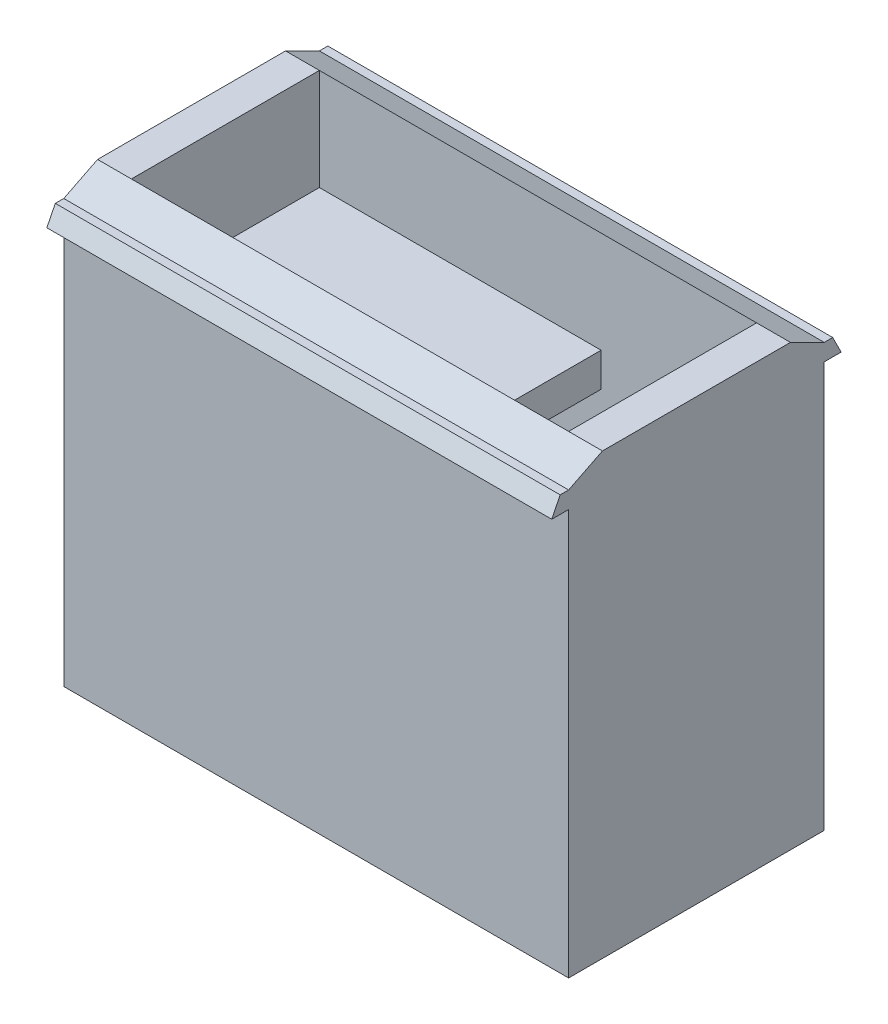
SolidWorks part; units mm, degrees
ref_plane "Front Plane" through (0, 0, 0) normal (0, 0, 1) x (1, 0, 0)
ref_plane "Top Plane" through (0, 0, 0) normal (0, 1, 0) x (1, 0, 0)
ref_plane "Right Plane" through (0, 0, 0) normal (1, 0, 0) x (0, 0, -1)
sketch "Sketch1" plane through (0, 0, 0) normal (0, 1, 0) x (1, 0, 0)
  line L0 (-13, 0) -> (-13, -1)
  line L1 (0, 0) -> (-13, 0)
  line L2 (0, 0) -> (0, 5.56)
  line L3 (0, 5.56) -> (-13, 5.56)
  line L4 (-13, 0) -> (-13, 5.56)
  line L5 (-13, -1) -> (0, -1)
  line L6 (0, 0) -> (1, 0)
  line L7 (0, -1) -> (1, -1)
  line L8 (1, -1) -> (1, 0)
  line L9 (1, 5.56) -> (1, 6.56)
  line L10 (1, 5.56) -> (1, 0)
  line L11 (1, 6.56) -> (-12.932, 6.56)
  line L12 (-12.932, 6.56) -> (-13.932, 6.56)
  line L13 (-13.932, 6.56) -> (-13.932, -1)
  line L14 (-13.932, -1) -> (-13, -1)
extrude "Boss-Extrude1" add sketch "Sketch1" along normal blind 10 contours L13 L14 L0 L4 L3 L2 L6 L10 L9 L11 L12 | L7 L8 L6 L1 L0 L5
sketch "Sketch2" plane through (0, 10, 0) normal (0, 1, 0) x (1, 0, 0)
  line L0 (-6.466, -1) -> (-6.466, 6.56)
  line L1 (-13.932, -1) -> (1, -1)
  line L2 (-13.932, -1) -> (-13.932, 6.56)
  line L3 (-13.932, 6.56) -> (1, 6.56)
  line L4 (1, -1) -> (1, 6.56)
  line L5 (-6.466, 2.78) -> (1, 2.78)
  line L6 (-6.466, 2.78) -> (-2.733, 2.78)
  line L7 (-2.733, 2.78) -> (-4.5995, 2.78)
  line L8 (-4.5995, 2.78) -> (-4.5995, 6.56)
  line L9 (-4.5995, 6.56) -> (-4.5995, -1)
  line L10 (-6.466, 6.56) -> (-13.932, 6.56)
  line M5 (-13.932, -1) -> (1, -1)
  line M7 (1, 6.56) -> (-13.932, 6.56)
  line M8 (-13.932, 6.56) -> (-13.932, -1)
  line M9 (0, 0) -> (-13, 0)
  line M10 (-13, 0) -> (-13, 5.56)
  line M11 (-13, 5.56) -> (0, 5.56)
extrude "Boss-Extrude2" add sketch "Sketch2" against normal blind 1 contours L0 M9 M11 M10 | L5 L8 L0 M11 | L9 L5 L0 M9 | L0 M5 M9 M10 M11 M7 M8 | L9 L0 M9 M5 | L8 L3 L0 M11
sketch "Sketch3" plane through (0, 10, 0) normal (0, 1, 0) x (1, 0, 0)
  line L0 (-13.932, 6.56) -> (-12.932, 6.56)
  line L1 (-13.932, -1) -> (1, -1)
  line L2 (-13.932, -1) -> (-13.932, 6.56)
  line L3 (-13.932, 6.56) -> (1, 6.56)
  line L4 (1, -1) -> (1, 6.56)
  line L5 (-12.932, 6.56) -> (-12.932, -1)
  line L6 (-12.932, -1) -> (-12.932, 0)
  line L7 (-12.932, 0) -> (-4.5995, 0)
  line L8 (-4.5995, 0) -> (0, 0)
  line L9 (0, 0) -> (0, 5.56)
  line L10 (0, 5.56) -> (-4.5995, 5.56)
  line L11 (-4.5995, 5.56) -> (-12.932, 5.56)
  line M6 (0, 0) -> (-4.5995, 0)
  line M8 (-4.5995, 5.56) -> (0, 5.56)
  line M9 (0, 5.56) -> (0, 0)
  line M10 (1, 6.56) -> (-13.932, 6.56)
  line M11 (-13.932, 6.56) -> (-13.932, -1)
  line M12 (-13.932, -1) -> (1, -1)
  line M13 (1, -1) -> (1, 6.56)
extrude "Boss-Extrude3" add sketch "Sketch3" along normal blind 3 contours L11 L7 L5 L1 M8 M9 M6 M13 M10 | L5 M10 M11 M12
sketch "Sketch4" plane through (0, 0, 1) normal (0, 0, 1) x (1, 0, 0)
  line L0 (1, 13) -> (1, 0) construction
  line L1 (-13.932, 13) -> (1, 13)
  line L2 (-13.932, 13) -> (-13.932, 12)
  line L3 (-13.932, 12) -> (1, 12)
  line L4 (1, 13) -> (1, 12)
extrude "Boss-Extrude4" add sketch "Sketch4" along normal blind 1
sketch "Sketch5" plane through (0, 0, -6.56) normal (0, 0, -1) x (-1, 0, 0)
  line L0 (13.932, 13) -> (13.932, 0) construction
  line L1 (-1, 13) -> (13.932, 13)
  line L2 (-1, 13) -> (-1, 12.0013)
  line L3 (-1, 12.0013) -> (13.932, 12.0013)
  line L4 (13.932, 13) -> (13.932, 12.0013)
extrude "Boss-Extrude5" add sketch "Sketch5" along normal blind 1
sketch "Sketch6" plane through (-13.932, 0, 0) normal (-1, 0, 0) x (0, 0, 1)
  line L0 (2, 12) -> (1, 12)
  line L1 (1, 12) -> (1, 13)
  line L2 (-7.56, 13) -> (2, 13) construction
  line L3 (1, 13) -> (2, 12)
  line L4 (2, 13) -> (1, 13)
  line L5 (2, 13) -> (2, 12)
  line L6 (-6.56, 12.0013) -> (-6.56, 13)
  line L7 (-6.56, 13) -> (-7.56, 13)
  line L8 (-7.56, 13) -> (-7.56, 12.0013)
  line L9 (-7.56, 12.0013) -> (-6.56, 12.0013)
  line L10 (-7.56, 13) -> (-6.56, 13)
  line L11 (-6.56, 13) -> (-7.56, 12.0013)
  line M1 (2, 13) -> (-7.56, 13)
  line M2 (-7.56, 13) -> (-7.56, 12.0013)
  line M8 (2, 12) -> (2, 13)
extrude "Cut-Extrude1" cut sketch "Sketch6" against normal blind 15 contours L11 M1 M2 | L3 M1 M8
sketch "Sketch7" plane through (1, 0, 0) normal (1, 0, 0) x (0, 0, -1)
  line L0 (-1, 13) -> (-1, 12)
  line L1 (-1, 12) -> (-1.5, 12)
  line L2 (-2, 12) -> (-1, 12) construction
  line L3 (-1.5, 12) -> (-1, 13)
  line L4 (-2, 12) -> (-1, 13)
  line L5 (-1.5, 12) -> (-2, 12)
  line L6 (6.56, 13) -> (6.56, 12.0013)
  line L7 (6.56, 12.0013) -> (7.06, 12.0013)
  line L8 (7.56, 12.0013) -> (6.56, 12.0013) construction
  line L9 (7.06, 12.0013) -> (6.56, 13)
  line L10 (7.56, 12.0013) -> (6.56, 13)
  line L11 (7.06, 12.0013) -> (7.56, 12.0013)
  line M1 (6.56, 12.0013) -> (7.56, 12.0013)
  line M2 (7.56, 12.0013) -> (6.56, 13)
  line M4 (-1, 13) -> (-2, 12)
  line M5 (-2, 12) -> (-1, 12)
extrude "Cut-Extrude2" cut sketch "Sketch7" against normal blind 15 contours L3 M5 M4 | L9 M1 M2
sketch "Sketch8" plane through (1, 0, 0) normal (1, 0, 0) x (0, 0, -1)
  line L0 (-1, 12) -> (6.56, 12.0013)
  line L1 (6.56, 12.0013) -> (6.56, 0) construction
sketch "Sketch9" plane through (0, 0, -6.56) normal (0, 0, -1) x (-1, 0, 0)
  line L0 (-1, 6.0007) -> (13.932, 6.0007)
  line L1 (-1, 12.0013) -> (-1, 0) construction
  line L2 (13.932, 12.0013) -> (13.932, 0) construction
  line L3 (-1, 12) -> (-1, 13) construction
sketch "Sketch10" plane through (1, 0, 0) normal (1, 0, 0) x (0, 0, -1)
  line L0 (-1.5, 12) -> (-1, 12)
  line L1 (5.56, 13) -> (5.56, 0) construction
sketch "Sketch11" plane through (0, 0, -5.56) normal (0, 0, 1) x (1, 0, 0)
  line L0 (-5.4355, 10) -> (-5.4355, 13)
  line L2 (-4.5995, 10) -> (-12.932, 10) construction
  line L3 (0, 13) -> (-12.932, 13) construction
sketch "Sketch12" plane through (-13.932, 0, 0) normal (-1, 0, 0) x (0, 0, 1)
  line L0 (-6.56, 12.0013) -> (-6.56, 13)
  line L1 (-6.56, 13) -> (-6.81, 12.5007)
  line L2 (-7.06, 12.0013) -> (-6.56, 13) construction
  line L3 (-6.81, 12.5007) -> (-6.56, 12.5007)
  line L4 (-6.56, 12.5007) -> (-5.56, 13)
  line L5 (-5.56, 13) -> (-6.56, 13)
  line L6 (1, 13) -> (1.25, 12.5)
  line L7 (1.5, 12) -> (1, 13) construction
  line L8 (1.25, 12.5) -> (1, 12.5)
  line L9 (1, 12.5) -> (1, 13)
  line L10 (0, 13) -> (1, 12.5)
  line L11 (-6.56, 13) -> (1, 13) construction
  line L12 (0, 13) -> (1, 13)
  line M6 (1.5, 12) -> (1, 13)
  line M7 (1, 13) -> (-6.56, 13)
extrude "Cut-Extrude3" cut sketch "Sketch12" against normal blind 15 contours L0 L4 M7 | L9 L8 M6 | L10 L9 M7
sketch "Sketch13" plane through (0, 10, 0) normal (0, 1, 0) x (1, 0, 0)
  line L0 (-4.5995, 2.78) -> (0, 2.78)
  line L1 (-4.5995, 5.56) -> (-4.5995, 0) construction
  line L2 (0, 5.56) -> (0, 0) construction
  line L3 (0, 2.78) -> (-12.932, 2.78)
  line L4 (-12.932, 5.56) -> (-12.932, 0) construction
sketch "Sketch15" plane through (-12.932, 0, 0) normal (1, 0, 0) x (0, 0, -1)
  line L0 (-1, 12) -> (0, 13)
  line L1 (0, 13) -> (0, 12.0002)
  line L2 (-1, 12) -> (6.56, 12.0013) construction
